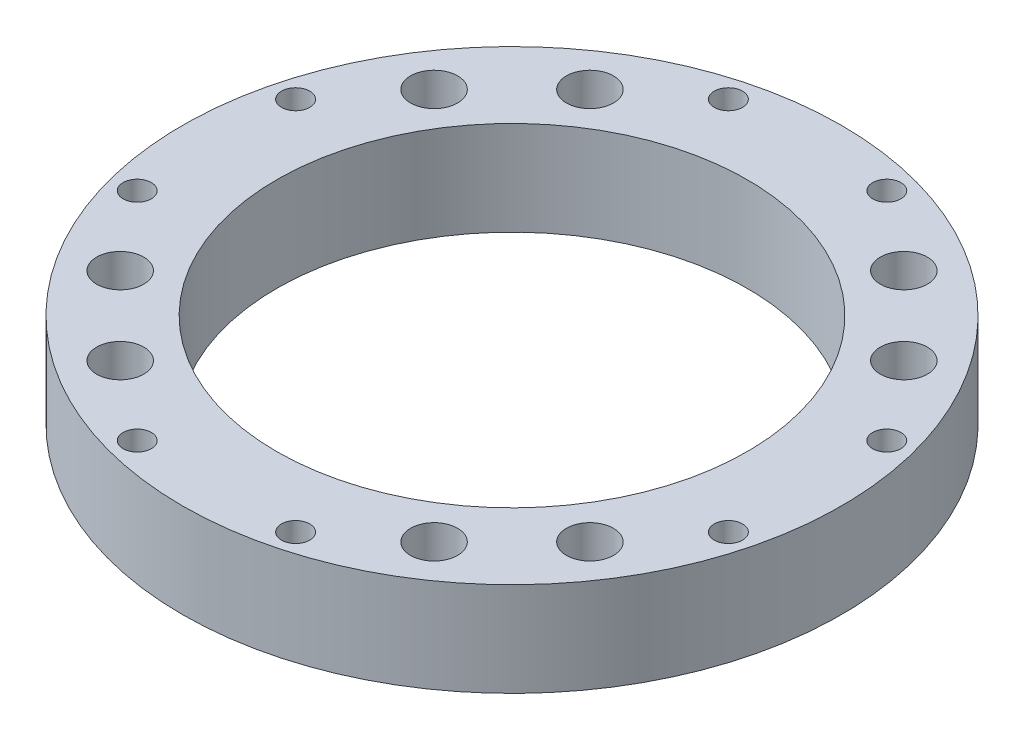
SolidWorks part; units mm, degrees
ref_plane "Front Plane" through (0, 0, 0) normal (0, 0, 1) x (1, 0, 0)
ref_plane "Top Plane" through (0, 0, 0) normal (0, 1, 0) x (1, 0, 0)
ref_plane "Right Plane" through (0, 0, 0) normal (1, 0, 0) x (0, 0, -1)
sketch "Sketch1" plane through (0, 0, 0) normal (0, 1, 0) x (1, 0, 0)
  line L0 (-8.4116, 31.3926) -> (0, 0) construction
  line L1 (0, 0) -> (15.7704, 0) construction
  line L2 (-24.9441, 16.6671) -> (0, 0) construction
  circle A0 centre (0, 0) radius 25
  circle A1 centre (0, 0) radius 35
  circle A2 centre (0, 0) radius 32.5 construction
  circle A3 centre (-8.4116, 31.3926) radius 1.5
  circle A4 centre (8.4116, 31.3926) radius 1.5
  circle A6 centre (31.3926, 8.4116) radius 1.5
  circle A7 centre (31.3926, -8.4116) radius 1.5
  circle A9 centre (8.4116, -31.3926) radius 1.5
  circle A10 centre (-8.4116, -31.3926) radius 1.5
  circle A12 centre (-31.3926, -8.4116) radius 1.5
  circle A13 centre (-31.3926, 8.4116) radius 1.5
  circle A15 centre (-22.981, 22.981) radius 1.5 [skipped]
  circle A16 centre (22.981, 22.981) radius 1.5 [skipped]
  circle A17 centre (22.981, -22.981) radius 1.5 [skipped]
  circle A18 centre (-22.981, -22.981) radius 1.5 [skipped]
  circle A20 centre (0, 0) radius 30 construction
  circle A21 centre (-24.9441, 16.6671) radius 2.5
  circle A22 centre (-16.6671, 24.9441) radius 2.5
  circle A25 centre (16.6671, 24.9441) radius 2.5
  circle A26 centre (24.9441, 16.6671) radius 2.5
  circle A29 centre (24.9441, -16.6671) radius 2.5
  circle A30 centre (16.6671, -24.9441) radius 2.5
  circle A33 centre (-16.6671, -24.9441) radius 2.5
  circle A34 centre (-24.9441, -16.6671) radius 2.5
  circle A37 centre (-5.8527, 29.4236) radius 2.5 [skipped]
  circle A38 centre (5.8527, 29.4236) radius 2.5 [skipped]
  circle A39 centre (29.4236, 5.8527) radius 2.5 [skipped]
  circle A40 centre (29.4236, -5.8527) radius 2.5 [skipped]
  circle A41 centre (5.8527, -29.4236) radius 2.5 [skipped]
  circle A42 centre (-5.8527, -29.4236) radius 2.5 [skipped]
  circle A43 centre (-29.4236, -5.8527) radius 2.5 [skipped]
  circle A44 centre (-29.4236, 5.8527) radius 2.5 [skipped]
  point P32 (0, 0)
  point P43 (0, 0)
  dimension "D1" = 70
  dimension "D2" = 50
  dimension "D3" = 65
  dimension "D4" = 3
  dimension "D8" = 5
  dimension "D9" = 146.25
  dimension "D7" = 60
  dimension "D5" = 105
  dimension "D6" = 12
  dimension "D10" = 16
extrude "Boss-Extrude1" add sketch "Sketch1" along normal blind 10
